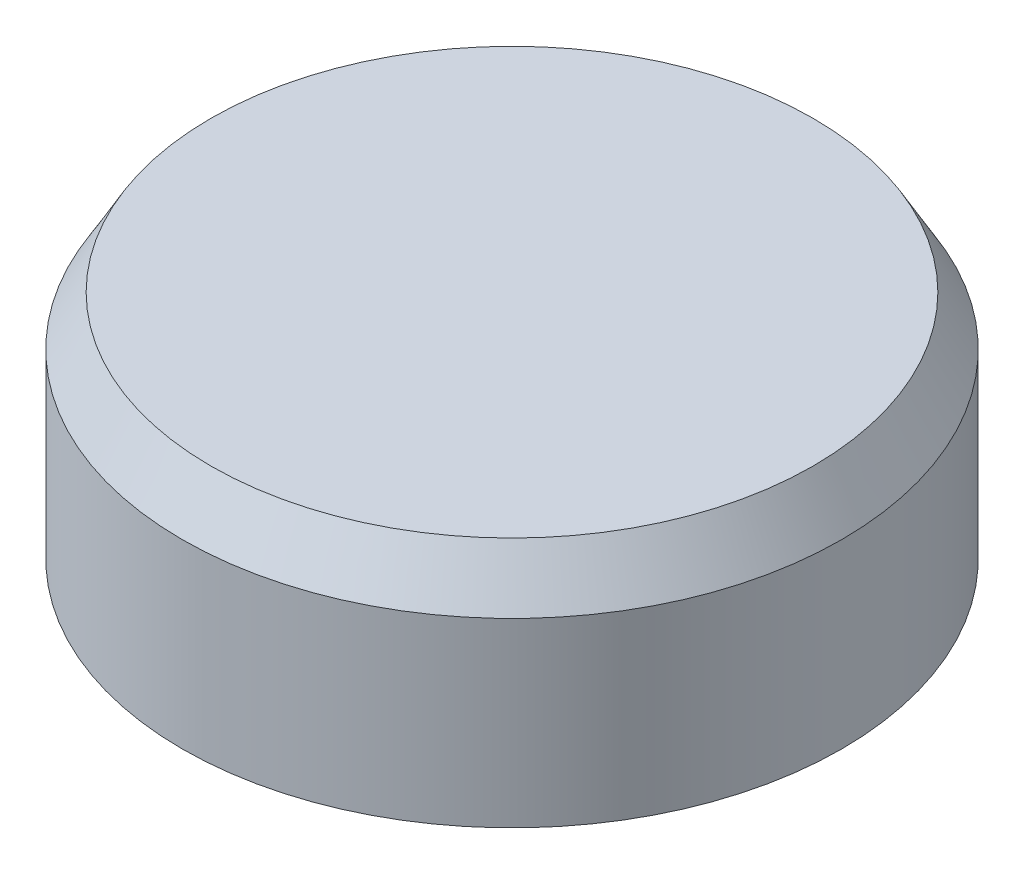
SolidWorks part; units mm, degrees
ref_plane "Front Plane" through (0, 0, 0) normal (0, 0, 1) x (1, 0, 0)
ref_plane "Top Plane" through (0, 0, 0) normal (0, 1, 0) x (1, 0, 0)
ref_plane "Right Plane" through (0, 0, 0) normal (1, 0, 0) x (0, 0, -1)
sketch "Sketch1" plane through (0, 0, 0) normal (0, 1, 0) x (1, 0, 0)
  circle A0 centre (0, 0) radius 10
  dimension "D1" = 20
extrude "Boss-Extrude1" add sketch "Sketch1" along normal blind 3
sketch "Sketch2" plane through (0, 0, 0) normal (0, -1, 0) x (1, 0, 0)
  circle A0 centre (0, 0) radius 3
  dimension "D1" = 6
extrude "Boss-Extrude2" add sketch "Sketch2" along normal blind 5.5
fillet "Fillet1" radius 0.5 1 edges at (0, 0, 3)
sketch "Sketch3" plane through (0, -5.5, 0) normal (0, -1, 0) x (1, 0, 0)
  line L0 (0.6, 0.6) -> (2.5, 0.6)
  line L1 (-2.5, 0.6) -> (-0.6, 0.6)
  line L2 (-2.5, 0.6) -> (-2.5, -0.6)
  line L3 (-2.5, -0.6) -> (-0.6, -0.6)
  line L4 (2.5, 0.6) -> (2.5, -0.6)
  line L7 (-0.6, 2.5) -> (0.6, 2.5)
  line L8 (-0.6, 2.5) -> (-0.6, 0.6)
  line L9 (-0.6, -2.5) -> (0.6, -2.5)
  line L10 (0.6, 2.5) -> (0.6, 0.6)
  line L17 (0.6, -0.6) -> (2.5, -0.6)
  line L19 (-0.6, -0.6) -> (-0.6, -2.5)
  line L20 (0.6, -0.6) -> (0.6, -2.5)
  point P0 (0, 0)
  point P1 (0, 0)
  point P6 (0, 0)
  point P8 (0, 0)
  dimension "D1" = 1.2
  dimension "D2" = 1.2
  dimension "D3" = 5
  dimension "D4" = 5
extrude "Cut-Extrude1" cut sketch "Sketch3" against normal blind 4.5
chamfer "Chamfer1" distance 1.5 angle 30 1 edges at (0, 3, 10)
sketch "Sketch4" plane through (0, 0, 0) normal (0, -1, 0) x (1, 0, 0)
  text T0 "<b>Ct</b>" font "Century Gothic" height in points 12
extrude "Cut-Extrude2" cut sketch "Sketch4" against normal blind 2
sketch "Sketch5" plane through (0, 0, 0) normal (0, -1, 0) x (1, 0, 0)
  circle A0 centre (0, 0) radius 8.5
  circle A1 centre (0, 0) radius 10
  circle A2 centre (0, 0) radius 10 construction
  dimension "D1" = 1.5
  dimension "D2" = 0
extrude "Boss-Extrude3" add sketch "Sketch5" along normal blind 4
chamfer "Chamfer2" distance 1 angle 45 1 edges at (0, -4, -8.5)
fillet "Fillet2" radius 0.5 8 edges at (0.6, -5.5, -1.55) (-0.6, -5.5, -1.55) (-1.55, -5.5, -0.6) (-1.55, -5.5, 0.6) (-0.6, -5.5, 1.55) (1.55, -5.5, -0.6) (1.55, -5.5, 0.6) (0.6, -5.5, 1.55)
